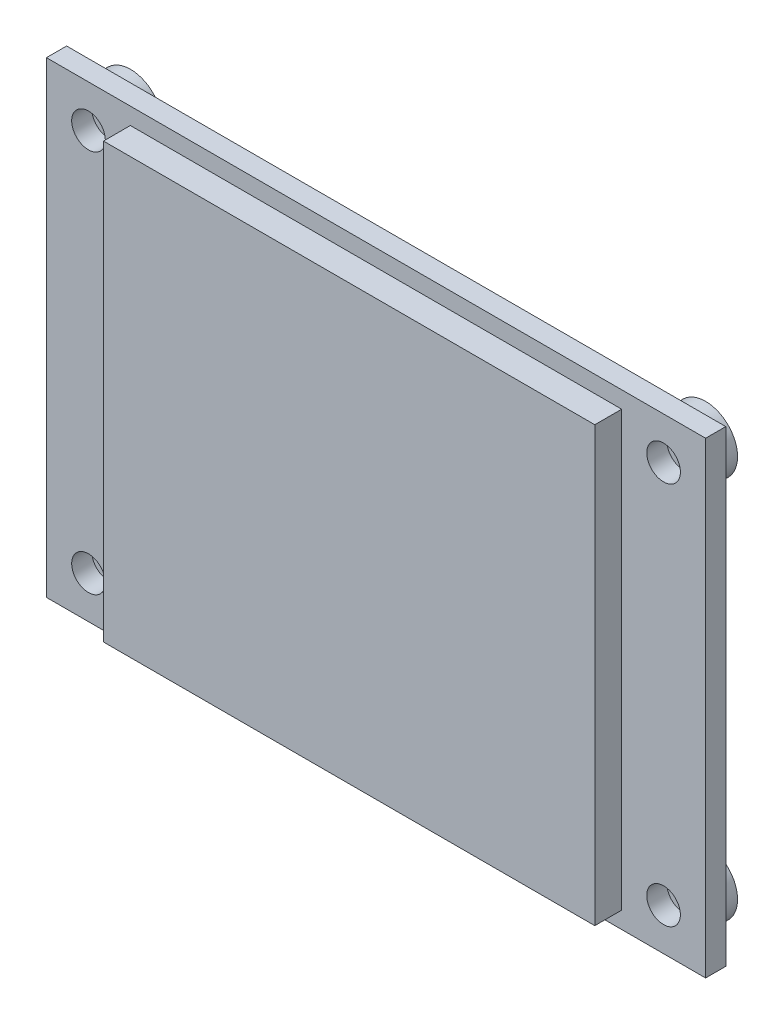
SolidWorks part; units mm, degrees
ref_plane "前基準面" through (0, 0, 0) normal (0, 0, 1) x (1, 0, 0)
ref_plane "上基準面" through (0, 0, 0) normal (0, 1, 0) x (1, 0, 0)
ref_plane "右基準面" through (0, 0, 0) normal (1, 0, 0) x (0, 0, -1)
sketch "草圖1" plane through (0, 0, 0) normal (0, 0, 1) x (1, 0, 0)
  line L0 (10.4, 31.1) -> (49.6, 31.1)
  line L1 (49.6, 31.1) -> (49.6, 58.9)
  line L2 (49.6, 58.9) -> (10.4, 58.9)
  line L3 (10.4, 58.9) -> (10.4, 31.1)
extrude "module PCB" add sketch "草圖1" along normal blind 1.2 from offset 25.2
sketch "草圖2" plane through (0, 0, 0) normal (0, 0, 1) x (1, 0, 0)
  line L0 (15.39, 32.1) -> (44.61, 32.1)
  line L1 (44.61, 32.1) -> (44.61, 57.9)
  line L2 (44.61, 57.9) -> (15.39, 57.9)
  line L3 (15.39, 57.9) -> (15.39, 32.1)
extrude "backlight frame" add sketch "草圖2" along normal blind 1 from offset 26.4
sketch "草圖3" plane through (0, 0, 0) normal (0, 0, 1) x (1, 0, 0)
  line L0 (15.39, 32.1) -> (44.61, 32.1)
  line L1 (44.61, 32.1) -> (44.61, 57.9)
  line L2 (44.61, 57.9) -> (15.39, 57.9)
  line L3 (15.39, 57.9) -> (15.39, 32.1)
extrude "glass" add sketch "草圖3" along normal blind 0.6 from offset 27.4
sketch "草圖4" plane through (0, 0, 0) normal (0, 0, 1) x (1, 0, 0)
  line L0 (11.63, 36.11) -> (14.17, 36.11)
  line L1 (14.17, 36.11) -> (14.17, 53.89)
  line L2 (14.17, 53.89) -> (11.63, 53.89)
  line L3 (11.63, 53.89) -> (11.63, 36.11)
extrude "7-pin header plastic on the module back" add sketch "草圖4" along normal blind 2.54 from offset 22.66
sketch "草圖5" plane through (0, 0, 0) normal (0, 0, 1) x (1, 0, 0)
  circle A0 centre (12.9, 33.6) radius 1
  circle A1 centre (12.9, 56.4) radius 1
  circle A2 centre (47.1, 33.6) radius 1
  circle A3 centre (47.1, 56.4) radius 1
extrude "corner holes" cut sketch "草圖5" along normal through all
sketch "草圖6" plane through (0, 0, 0) normal (0, 0, 1) x (1, 0, 0)
  circle A0 centre (12.9, 33.6) radius 1.9
extrude "M2 screw head" add sketch "草圖6" along normal blind 1.3 from offset 23.9
sketch "草圖7" plane through (0, 0, 0) normal (0, 0, 1) x (1, 0, 0)
  circle A0 centre (12.9, 56.4) radius 1.9
extrude "填料-伸長6" add sketch "草圖7" along normal blind 1.3 from offset 23.9
sketch "草圖8" plane through (0, 0, 0) normal (0, 0, 1) x (1, 0, 0)
  circle A0 centre (47.1, 33.6) radius 1.9
extrude "填料-伸長7" add sketch "草圖8" along normal blind 1.3 from offset 23.9
sketch "草圖9" plane through (0, 0, 0) normal (0, 0, 1) x (1, 0, 0)
  circle A0 centre (47.1, 56.4) radius 1.9
extrude "填料-伸長8" add sketch "草圖9" along normal blind 1.3 from offset 23.9
